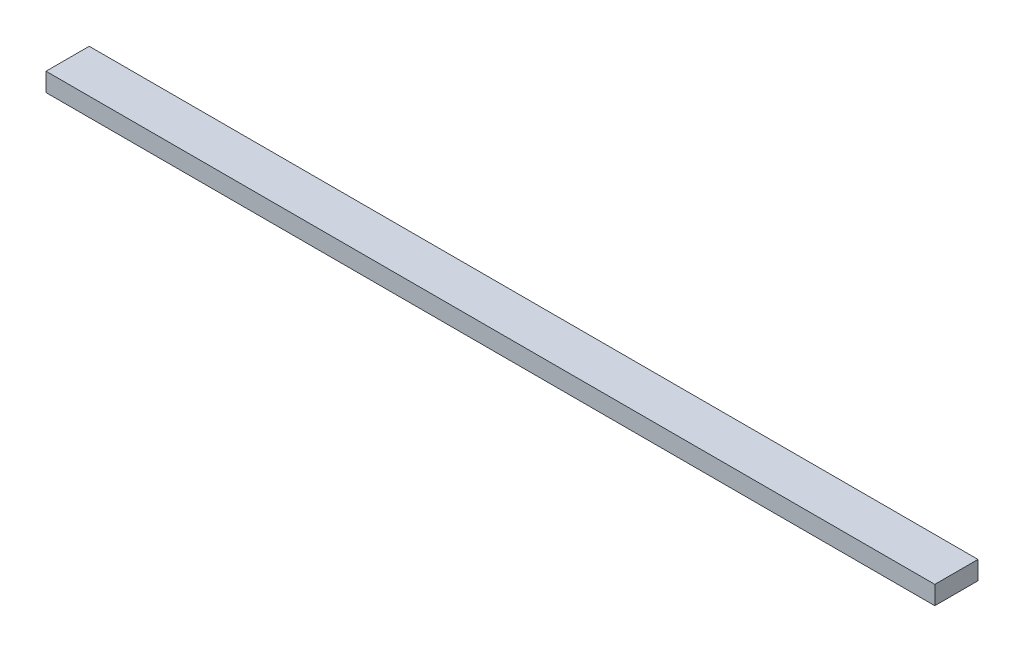
SolidWorks part; units mm, degrees
ref_plane "Front Plane" through (0, 0, 0) normal (0, 0, 1) x (1, 0, 0)
ref_plane "Top Plane" through (0, 0, 0) normal (0, 1, 0) x (1, 0, 0)
ref_plane "Right Plane" through (0, 0, 0) normal (1, 0, 0) x (0, 0, -1)
sketch "Sketch1" plane through (0, 0, 0) normal (0, 1, 0) x (1, 0, 0)
  line L0 (1828.8, 88.9) -> (1828.8, 0)
  line L1 (0, 0) -> (1828.8, 0)
  line L2 (0, 0) -> (0, 88.9)
  line L3 (0, 88.9) -> (1828.8, 88.9)
  line L5 (1568.45, 88.9) -> (1568.45, 0) construction
  line L6 (1479.55, 88.9) -> (1479.55, 0) construction
  line L7 (1390.65, 88.9) -> (1390.65, 0) construction
  line L8 (1301.75, 88.9) -> (1301.75, 0) construction
  line L9 (1212.85, 88.9) -> (1212.85, 0) construction
  line L10 (1123.95, 88.9) -> (1123.95, 0) construction
  line L11 (1035.05, 88.9) -> (1035.05, 0) construction
  line L12 (946.15, 88.9) -> (946.15, 0) construction
  line L13 (857.25, 88.9) -> (857.25, 0) construction
  line L14 (768.35, 88.9) -> (768.35, 0) construction
  line L15 (679.45, 88.9) -> (679.45, 0) construction
  line L16 (590.55, 88.9) -> (590.55, 0) construction
  line L17 (501.65, 88.9) -> (501.65, 0) construction
  line L18 (412.75, 88.9) -> (412.75, 0) construction
  line L19 (323.85, 88.9) -> (323.85, 0) construction
  line L20 (234.95, 88.9) -> (234.95, 0) construction
  line L22 (146.05, 88.9) -> (146.05, 0) [skipped]
  dimension "D1" = 88.9
  dimension "D2" = 1828.8
  dimension "D3" = 90
  dimension "D4" = 17
  dimension "D5" = 260.35
  dimension "D6" = 349.25
  dimension "D7" = 438.15
  dimension "D8" = 527.05
  dimension "D9" = 615.95
  dimension "D10" = 704.85
  dimension "D11" = 793.75
  dimension "D12" = 882.65
  dimension "D13" = 971.55
  dimension "D14" = 88.9
  dimension "D15" = 1060.45
  dimension "D16" = 1149.35
  dimension "D17" = 1238.25
  dimension "D18" = 1327.15
  dimension "D20" = 1593.85
extrude "Boss-Extrude1" add sketch "Sketch1" against normal blind 38.1
